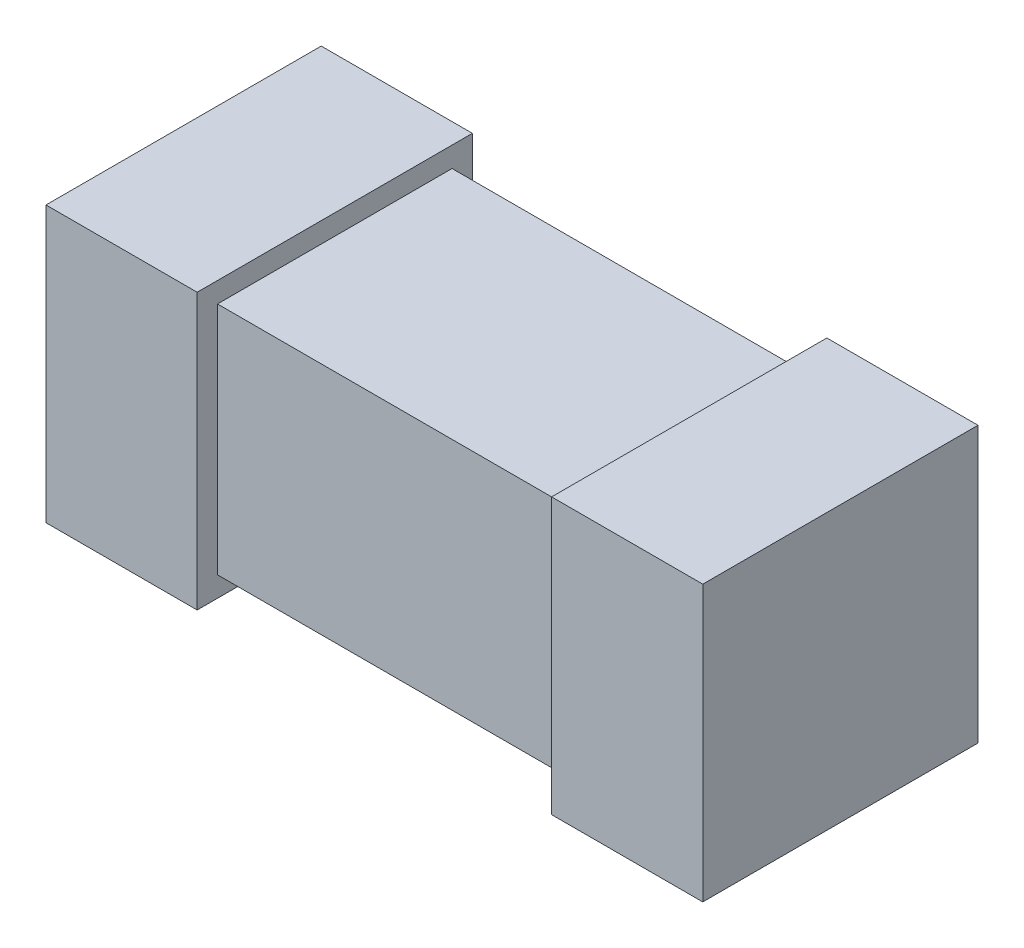
SolidWorks part; units mm, degrees
ref_plane "Front Plane" through (0, 0, 0) normal (0, 0, 1) x (1, 0, 0)
ref_plane "Top Plane" through (0, 0, 0) normal (0, 1, 0) x (1, 0, 0)
ref_plane "Right Plane" through (0, 0, 0) normal (1, 0, 0) x (0, 0, -1)
sketch "Sketch1" plane through (0, 0, 0) normal (1, 0, 0) x (0, 0, -1)
  line L1 (-1.125, 1.125) -> (1.125, 1.125)
  line L2 (-1.125, 1.125) -> (-1.125, -1.125)
  line L3 (-1.125, -1.125) -> (1.125, -1.125)
  line L4 (1.125, 1.125) -> (1.125, -1.125)
  line L5 (-1.125, 1.125) -> (1.125, -1.125) construction
  line L6 (-1.125, -1.125) -> (1.125, 1.125) construction
  point P0 (0, 0)
  dimension "D1" = 2.25
extrude "Boss-Extrude1" add sketch "Sketch1" along normal mid plane 3.4
sketch "Sketch2" plane through (1.7, 0, 0) normal (1, 0, 0) x (0, 0, -1)
  line L1 (-1.32, 1.32) -> (1.32, 1.32)
  line L2 (-1.32, 1.32) -> (-1.32, -1.32)
  line L3 (-1.32, -1.32) -> (1.32, -1.32)
  line L4 (1.32, 1.32) -> (1.32, -1.32)
  line L5 (-1.32, 1.32) -> (1.32, -1.32) construction
  line L6 (-1.32, -1.32) -> (1.32, 1.32) construction
  point P0 (0, 0)
  dimension "D1" = 2.64
extrude "Boss-Extrude2" add sketch "Sketch2" along normal blind 1.45
mirror "Mirror1" about plane through (0, 0, 0) normal (1, 0, 0) of "Boss-Extrude2"
equation "\"D1@Boss-Extrude1\"=6.1-(1.35*2)"
